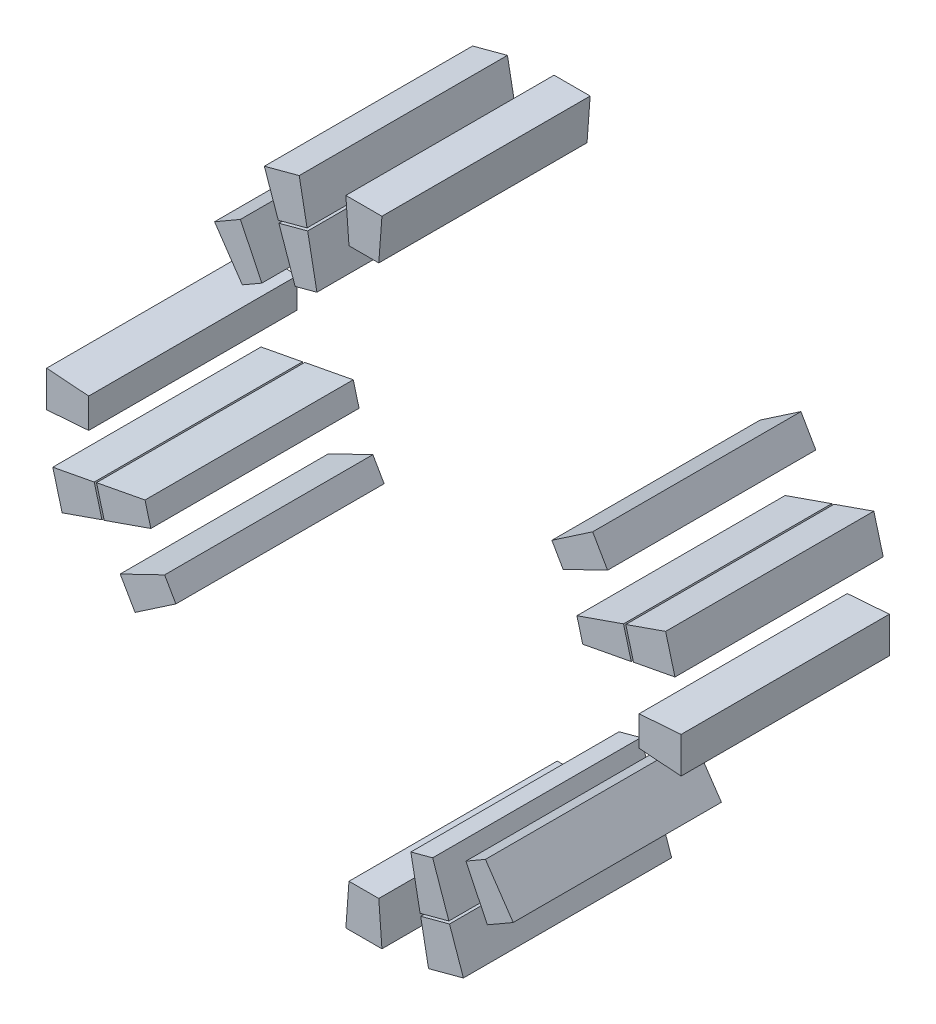
SolidWorks part; units mm, degrees
ref_plane "Спереди" through (0, 0, 0) normal (0, 0, 1) x (1, 0, 0)
ref_plane "Сверху" through (0, 0, 0) normal (0, 1, 0) x (1, 0, 0)
ref_plane "Справа" through (0, 0, 0) normal (1, 0, 0) x (0, 0, -1)
sketch "Эскиз1" plane through (0, 0, 0) normal (0, 0, 1) x (1, 0, 0)
  line L0 (39.6419, -2.1473) -> (45.7, -2.6)
  line L1 (45.7, -2.6) -> (45.7, 2.6)
  line L2 (45.7, 2.6) -> (39.6419, 2.1473)
  line L3 (39.6419, 2.1473) -> (39.6419, -2.1473)
  line L4 (31.5321, 6.7667) -> (38.5167, 8.0974)
  line L5 (38.5167, 8.0974) -> (37.4051, 12.2457)
  line L6 (37.4051, 12.2457) -> (30.691, 9.9059)
  line L7 (30.691, 9.9059) -> (31.5321, 6.7667)
  line L8 (38.8469, 8.1859) -> (44.8157, 9.3166)
  line L9 (44.8157, 9.3166) -> (43.4699, 14.3394)
  line L10 (43.4699, 14.3394) -> (37.7354, 12.3342)
  line L11 (37.7354, 12.3342) -> (38.8469, 8.1859)
  line L12 (28.7063, 14.6972) -> (35.1085, 17.7904)
  line L13 (35.1085, 17.7904) -> (32.9611, 21.5096)
  line L14 (32.9611, 21.5096) -> (27.0813, 17.5118)
  line L15 (27.0813, 17.5118) -> (28.7063, 14.6972)
  line L16 (2.1473, 39.6419) -> (2.6, 45.7)
  line L17 (2.6, 45.7) -> (-2.6, 45.7)
  line L18 (-2.6, 45.7) -> (-2.1473, 39.6419)
  line L19 (-2.1473, 39.6419) -> (2.1473, 39.6419)
  line L20 (-6.7667, 31.5321) -> (-8.0974, 38.5167)
  line L21 (-8.0974, 38.5167) -> (-12.2457, 37.4051)
  line L22 (-12.2457, 37.4051) -> (-9.9059, 30.691)
  line L23 (-9.9059, 30.691) -> (-6.7667, 31.5321)
  line L24 (-8.1859, 38.8469) -> (-9.3166, 44.8157)
  line L25 (-9.3166, 44.8157) -> (-14.3394, 43.4699)
  line L26 (-14.3394, 43.4699) -> (-12.3342, 37.7354)
  line L27 (-12.3342, 37.7354) -> (-8.1859, 38.8469)
  line L28 (-14.6972, 28.7063) -> (-17.7904, 35.1085)
  line L29 (-17.7904, 35.1085) -> (-21.5096, 32.9611)
  line L30 (-21.5096, 32.9611) -> (-17.5118, 27.0813)
  line L31 (-17.5118, 27.0813) -> (-14.6972, 28.7063)
  line L32 (-39.6419, 2.1473) -> (-45.7, 2.6)
  line L33 (-45.7, 2.6) -> (-45.7, -2.6)
  line L34 (-45.7, -2.6) -> (-39.6419, -2.1473)
  line L35 (-39.6419, -2.1473) -> (-39.6419, 2.1473)
  line L36 (-31.5321, -6.7667) -> (-38.5167, -8.0974)
  line L37 (-38.5167, -8.0974) -> (-37.4051, -12.2457)
  line L38 (-37.4051, -12.2457) -> (-30.691, -9.9059)
  line L39 (-30.691, -9.9059) -> (-31.5321, -6.7667)
  line L40 (-38.8469, -8.1859) -> (-44.8157, -9.3166)
  line L41 (-44.8157, -9.3166) -> (-43.4699, -14.3394)
  line L42 (-43.4699, -14.3394) -> (-37.7354, -12.3342)
  line L43 (-37.7354, -12.3342) -> (-38.8469, -8.1859)
  line L44 (-28.7063, -14.6972) -> (-35.1085, -17.7904)
  line L45 (-35.1085, -17.7904) -> (-32.9611, -21.5096)
  line L46 (-32.9611, -21.5096) -> (-27.0813, -17.5118)
  line L47 (-27.0813, -17.5118) -> (-28.7063, -14.6972)
  line L48 (-2.1473, -39.6419) -> (-2.6, -45.7)
  line L49 (-2.6, -45.7) -> (2.6, -45.7)
  line L50 (2.6, -45.7) -> (2.1473, -39.6419)
  line L51 (2.1473, -39.6419) -> (-2.1473, -39.6419)
  line L52 (6.7667, -31.5321) -> (8.0974, -38.5167)
  line L53 (8.0974, -38.5167) -> (12.2457, -37.4051)
  line L54 (12.2457, -37.4051) -> (9.9059, -30.691)
  line L55 (9.9059, -30.691) -> (6.7667, -31.5321)
  line L56 (8.1859, -38.8469) -> (9.3166, -44.8157)
  line L57 (9.3166, -44.8157) -> (14.3394, -43.4699)
  line L58 (14.3394, -43.4699) -> (12.3342, -37.7354)
  line L59 (12.3342, -37.7354) -> (8.1859, -38.8469)
  line L60 (14.6972, -28.7063) -> (17.7904, -35.1085)
  line L61 (17.7904, -35.1085) -> (21.5096, -32.9611)
  line L62 (21.5096, -32.9611) -> (17.5118, -27.0813)
  line L63 (17.5118, -27.0813) -> (14.6972, -28.7063)
extrude "Coil_sides" add sketch "Эскиз1" along normal blind 30 from offset 15 separate body
